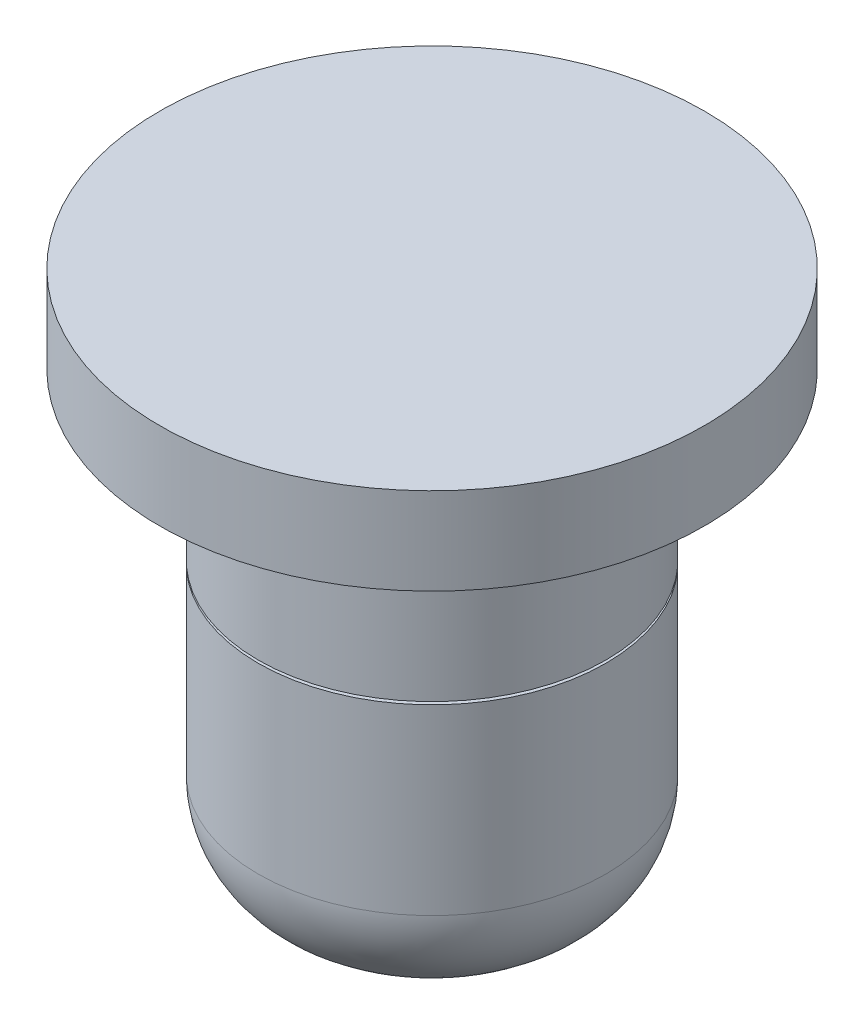
SolidWorks part; units mm, degrees
ref_plane "Front Plane" through (0, 0, 0) normal (0, 0, 1) x (1, 0, 0)
ref_plane "Top Plane" through (0, 0, 0) normal (0, 1, 0) x (1, 0, 0)
ref_plane "Right Plane" through (0, 0, 0) normal (1, 0, 0) x (0, 0, -1)
sketch "Sketch1" plane through (0, 0, 0) normal (0, 0, 1) x (1, 0, 0)
  line L0 (0, 18.6267) -> (19.8967, 18.6267)
  line L1 (19.8967, 18.6267) -> (19.8967, 12.2767)
  line L2 (19.8967, 12.2767) -> (12.7, 12.2767)
  line L3 (12.7, 12.2767) -> (12.7, -13.335)
  line L4 (5.08, -20.955) -> (0, -20.955)
  line L5 (0, -20.955) -> (0, 18.6267)
  arc A0 (12.7, -13.335) -> (5.08, -20.955) centre (5.08, -13.335) cw
  point P9 (12.7, -20.955)
  dimension "D2" = 7.62
  dimension "D1" = 12.7
revolve "Revolve1" add sketch "Sketch1" angle 360 about L5
sketch "Sketch2" plane through (0, 0, 0) normal (0, 0, 1) x (1, 0, 0)
  line L1 (-36.4156, 0) -> (36.4156, 0)
  line L2 (-36.4156, 0) -> (-36.4156, 0.2)
  line L3 (-36.4156, 0.2) -> (36.4156, 0.2)
  line L4 (36.4156, 0) -> (36.4156, 0.2)
  dimension "D1" = 0.2
extrude "Cut-Extrude1" cut sketch "Sketch2" against normal through all both and the other way through all
